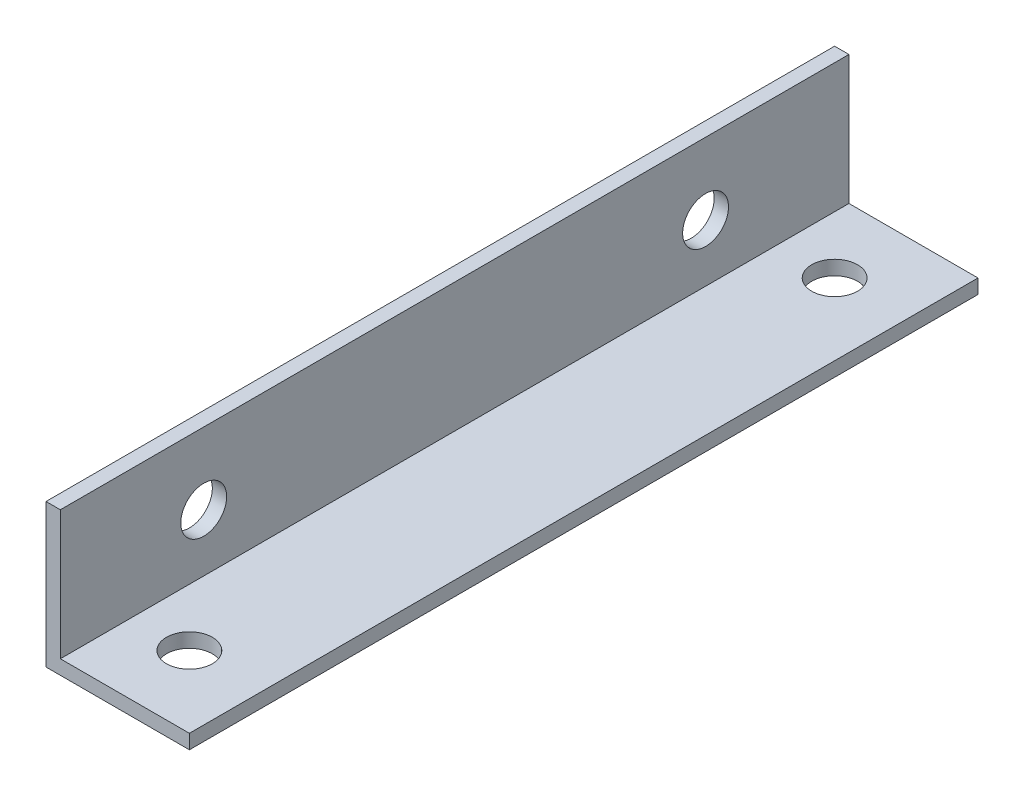
SolidWorks part; units mm, degrees
ref_plane "正面" through (0, 0, 0) normal (0, 0, 1) x (1, 0, 0)
ref_plane "平面" through (0, 0, 0) normal (0, 1, 0) x (1, 0, 0)
ref_plane "右側面" through (0, 0, 0) normal (1, 0, 0) x (0, 0, -1)
sketch "ｽｹｯﾁ1" plane through (0, 0, 0) normal (0, 0, 1) x (1, 0, 0)
  line L0 (-4, 5) -> (-4, -4)
  line L1 (5, -5) -> (-5, -5)
  line L2 (5, -5) -> (5, -4)
  line L3 (-4, 5) -> (-5, 5)
  line L4 (-5, -5) -> (-5, 5)
  line L5 (5, -5) -> (-5, 5) construction
  line L6 (5, 5) -> (-5, -5) construction
  line L7 (-4, -4) -> (5, -4)
  point P0 (0, 0)
  dimension "D1" = 10
  dimension "D2" = 10
  dimension "D3" = 1
  dimension "D4" = 10
extrude "ﾎﾞｽ - 押し出し1" add sketch "ｽｹｯﾁ1" along normal blind 55
sketch "ｽｹｯﾁ2" plane through (0, -5, 0) normal (0, -1, 0) x (1, 0, 0)
  line L0 (0, 0) -> (0, 55) construction
  line L1 (-5, 0) -> (5, 0) construction
  line L2 (-5, 55) -> (5, 55) construction
  circle A0 centre (0, 5) radius 1.6
  circle A1 centre (0, 50) radius 1.6
  dimension "D1" = 5
  dimension "D2" = 5
  dimension "D3" = 3.2
extrude "ｶｯﾄ - 押し出し1" cut sketch "ｽｹｯﾁ2" against normal through all
sketch "ｽｹｯﾁ3" plane through (-5, 0, 0) normal (-1, 0, 0) x (0, 0, 1)
  line L0 (0, 0) -> (55, 0) construction
  line L1 (0, 5) -> (0, -5) construction
  line L2 (55, 5) -> (55, -5) construction
  circle A0 centre (10, 0) radius 1.6
  circle A1 centre (45, 0) radius 1.6
  point P10 (27.5, 0)
  dimension "D1" = 3.2
  dimension "D2" = 17.5
  dimension "D3" = 35
extrude "ｶｯﾄ - 押し出し2" cut sketch "ｽｹｯﾁ3" against normal through all
